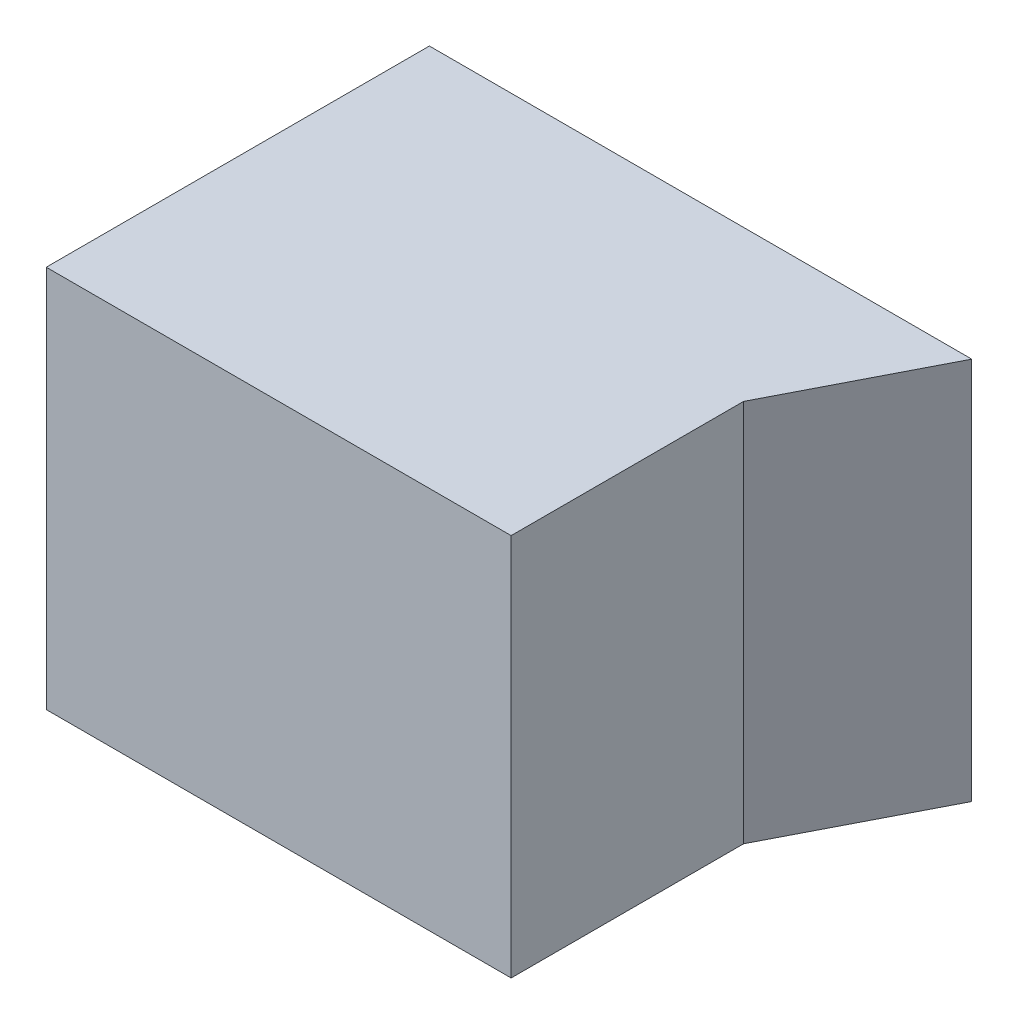
SolidWorks part; units mm, degrees
ref_plane "Front Plane" through (0, 0, 0) normal (0, 0, 1) x (1, 0, 0)
ref_plane "Top Plane" through (0, 0, 0) normal (0, 1, 0) x (1, 0, 0)
ref_plane "Right Plane" through (0, 0, 0) normal (1, 0, 0) x (0, 0, -1)
sketch "Sketch1" plane through (0, 0, 0) normal (0, 1, 0) x (1, 0, 0)
  line L1 (38.1, -25.4) -> (-38.1, -25.4)
  line L2 (38.1, -25.4) -> (38.1, 25.4)
  line L3 (38.1, 25.4) -> (-38.1, 25.4)
  line L4 (-38.1, -25.4) -> (-38.1, 25.4)
  line L5 (38.1, -25.4) -> (-38.1, 25.4) construction
  line L6 (38.1, 25.4) -> (-38.1, -25.4) construction
  point P0 (0, 0)
  dimension "D1" = 76.2
  dimension "D2" = 50.8
sketch "Sketch10" plane through (0, 0, 0) normal (1, 0, 0) x (0, 0, -1)
  line L0 (-12.7, 0) -> (0, 0) construction
  line L1 (0, 0) -> (0, -12.7) construction
  line L2 (0, 0) -> (0, 12.7) construction
  line L3 (0, 0) -> (12.7, 0) construction
  line L4 (6.35, 10.16) -> (-6.35, 10.16)
  line L5 (-6.5427, 9.7405) -> (-2.54, 5.08)
  line L6 (6.5427, 9.7405) -> (2.54, 5.08)
  line L7 (2.54, 5.08) -> (-2.54, 5.08)
  line L8 (-5.08, -2.54) -> (-5.08, 2.54)
  line L9 (-5.08, 2.54) -> (-9.7405, 6.5427)
  line L10 (-10.16, -6.35) -> (-10.16, 6.35)
  line L11 (-9.7405, -6.5427) -> (-5.08, -2.54)
  line L12 (-12.7, -2.54) -> (-12.7, 2.54)
  line L13 (-12.7, 2.54) -> (-10.16, 2.54)
  line L14 (-10.16, 2.54) -> (-10.16, -2.54)
  line L15 (-10.16, -2.54) -> (-12.7, -2.54)
  line L16 (2.54, 12.7) -> (-2.54, 12.7)
  line L17 (-2.54, 12.7) -> (-2.54, 10.16)
  line L18 (-2.54, 10.16) -> (2.54, 10.16)
  line L19 (2.54, 10.16) -> (2.54, 12.7)
  line L20 (2.54, -12.7) -> (-2.54, -12.7)
  line L21 (2.54, -5.08) -> (-2.54, -5.08)
  line L23 (6.35, -10.16) -> (-6.35, -10.16)
  line L24 (-2.54, -12.7) -> (-2.54, -10.16)
  line L26 (2.54, -12.7) -> (2.54, -10.16)
  line L27 (-2.54, -10.16) -> (2.54, -10.16)
  line L28 (-2.54, -5.08) -> (-6.5427, -9.7405)
  line L29 (2.54, -5.08) -> (6.5427, -9.7405)
  line L30 (5.08, -2.54) -> (5.08, 2.54)
  line L31 (12.7, -2.54) -> (12.7, 2.54)
  line L32 (12.7, 2.54) -> (10.16, 2.54)
  line L33 (10.16, 2.54) -> (10.16, -2.54)
  line L34 (10.16, -2.54) -> (12.7, -2.54)
  line L35 (10.16, -6.35) -> (10.16, 6.35)
  line L36 (5.08, 2.54) -> (9.7405, 6.5427)
  line L37 (5.08, -2.54) -> (9.7405, -6.5427)
  arc A0 (-10.16, -6.35) -> (-9.7405, -6.5427) centre (-9.906, -6.35) ccw
  arc A1 (-9.7405, 6.5427) -> (-10.16, 6.35) centre (-9.906, 6.35) ccw
  arc A2 (6.35, 10.16) -> (6.5427, 9.7405) centre (6.35, 9.906) cw
  arc A3 (-6.35, 10.16) -> (-6.5427, 9.7405) centre (-6.35, 9.906) ccw
  arc A4 (-6.35, -10.16) -> (-6.5427, -9.7405) centre (-6.35, -9.906) cw
  arc A6 (6.5427, -9.7405) -> (6.35, -10.16) centre (6.35, -9.906) cw
  arc A8 (9.7405, -6.5427) -> (10.16, -6.35) centre (9.906, -6.35) ccw
  arc A9 (10.16, 6.35) -> (9.7405, 6.5427) centre (9.906, 6.35) ccw
  point P4 (0, 5.08)
  point P10 (0, 10.16)
  point P17 (-5.08, 0)
  point P20 (-10.16, 0)
  point P30 (-12.7, 0)
  point P35 (0, 12.7)
  point P39 (0, -12.7)
  point P42 (0, -5.08)
  point P46 (0, -10.16)
  point P52 (5.08, 0)
  point P55 (12.7, 0)
  point P60 (10.16, 0)
  dimension "D1" = 0.254
  dimension "D16" = 0.254
  dimension "D2" = 5.08
  dimension "D3" = 5.08
  dimension "D4" = 2.54
  dimension "D5" = 2.54
  dimension "D6" = 5.08
  dimension "D7" = 12.7
  dimension "D8" = 5.08
  dimension "D9" = 12.7
  dimension "D10" = 5.08
  dimension "D11" = 5.08
  dimension "D12" = 12.7
  dimension "D13" = 5.08
  dimension "D14" = 5.08
  dimension "D15" = 2.54
extrude "Boss-Extrude3" add sketch "Sketch10" against normal blind 25.4 separate body
sketch "Sketch11" plane through (0, 0, 0) normal (1, 0, 0) x (0, 0, -1)
  line L0 (2.54, -12.7) -> (-2.54, -12.7) construction
  line L1 (-12.7, 12.7) -> (12.7, 12.7)
  line L2 (-12.7, 12.7) -> (-12.7, -12.7)
  line L3 (-12.7, -12.7) -> (12.7, -12.7)
  line L4 (12.7, 12.7) -> (12.7, -12.7)
  line L5 (-12.7, 12.7) -> (12.7, -12.7) construction
  line L6 (-12.7, -12.7) -> (12.7, 12.7) construction
  line L7 (-12.7, -2.54) -> (-12.7, 2.54) construction
  line L8 (-15.7, 0) -> (-12.7, 0) construction
  line L9 (15.7, -15.7) -> (-15.7, -15.7)
  line L10 (15.7, -15.7) -> (15.7, 15.7)
  line L11 (15.7, 15.7) -> (-15.7, 15.7)
  line L12 (-15.7, -15.7) -> (-15.7, 15.7)
  line L13 (15.7, -15.7) -> (-15.7, 15.7) construction
  line L14 (15.7, 15.7) -> (-15.7, -15.7) construction
  line L15 (0, 12.7) -> (0, 15.7) construction
  point P0 (0, 0)
  point P10 (0, 0)
  dimension "D1" = 3
extrude "Boss-Extrude5" add sketch "Sketch11" against normal through all
sketch "Sketch13" plane through (0, -15.7, 0) normal (0, -1, 0) x (1, 0, 0)
  line L0 (0, 15.7) -> (12.7, 15.7)
  line L1 (12.7, 15.7) -> (12.7, -3.35)
  line L2 (12.7, -3.35) -> (19.05, -15.7)
  line L3 (19.05, -15.7) -> (0, -15.7)
  line L4 (0, 15.7) -> (0, -15.7)
  dimension "D1" = 19.05
  dimension "D2" = 12.7
  dimension "D3" = 19.05
extrude "Boss-Extrude6" add sketch "Sketch13" against normal through all
